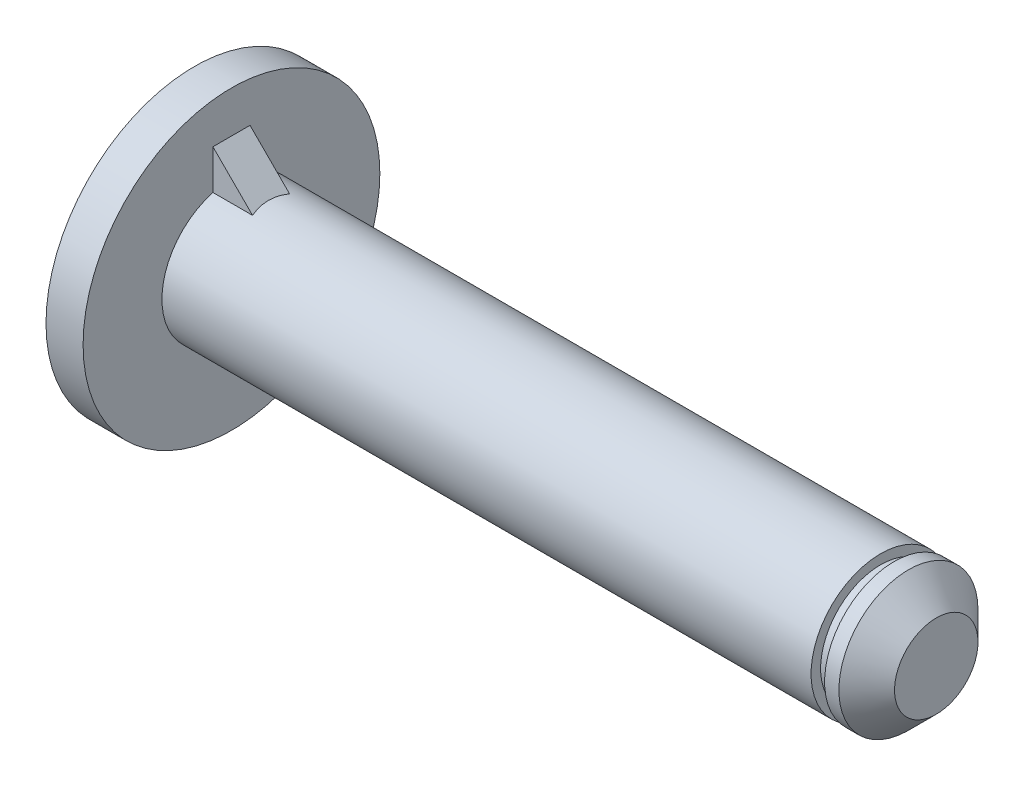
SolidWorks part; units mm, degrees
ref_plane "Front Plane" through (0, 0, 0) normal (0, 0, 1) x (1, 0, 0)
ref_plane "Top Plane" through (0, 0, 0) normal (0, 1, 0) x (1, 0, 0)
ref_plane "Right Plane" through (0, 0, 0) normal (1, 0, 0) x (0, 0, -1)
sketch "Sketch1" plane through (0, 0, 0) normal (0, 0, 1) x (1, 0, 0)
  line L0 (0, 0) -> (2, 0)
  line L1 (2, 0) -> (2, 4.25)
  line L2 (2, 4.25) -> (37, 4.25)
  line L7 (40, 4.25) -> (40, 8)
  line L8 (40, 8) -> (0, 8)
  line L9 (0, 8) -> (0, 0)
  line L10 (-10.1111, 8) -> (25.9444, 8) construction
  line L11 (37, 4.25) -> (40, 4.25)
  dimension "D1" = 2
  dimension "D2" = 40
  dimension "D4" = 8
  dimension "D5" = 3.75
revolve "Revolve1" add sketch "Sketch1" angle 360 about L10
sketch "Sketch7" plane through (0, 0, 0) normal (0, 0, 1) x (1, 0, 0)
  line L0 (2, 13.75) -> (4, 11.75)
  line L1 (2, 0) -> (2, 16) construction
  line L2 (40, 11.75) -> (2, 11.75) construction
  dimension "D1" = 2
  dimension "D2" = 2
rib "Rib11" sketch "Sketch7" sketch "Sketch7" thickness 2 extrusion direction parallel to sketch draft on no parameters "D1"=2
chamfer "Chamfer1" distance 1.5 angle 45 1 edges at (40, 8, 3.75)
sketch "Sketch8" plane through (0, 0, 0) normal (0, 0, 1) x (1, 0, 0)
  line L0 (37, 11.75) -> (37, 11.235)
  line L1 (38.5, 11.75) -> (4, 11.75) construction
  line L2 (37, 11.235) -> (37.73, 11.235)
  line L3 (37.73, 11.235) -> (37.73, 11.75)
  line L4 (37.73, 11.75) -> (37, 11.75)
  line L5 (40, 8) -> (23.2556, 8) construction
  line L6 (40, 5.75) -> (40, 10.25) construction
  dimension "D1" = 0.73
  dimension "D2" = 2.27
  dimension "D3" = 3.235
revolve "Cut-Revolve1" cut sketch "Sketch8" angle 360 about L5
